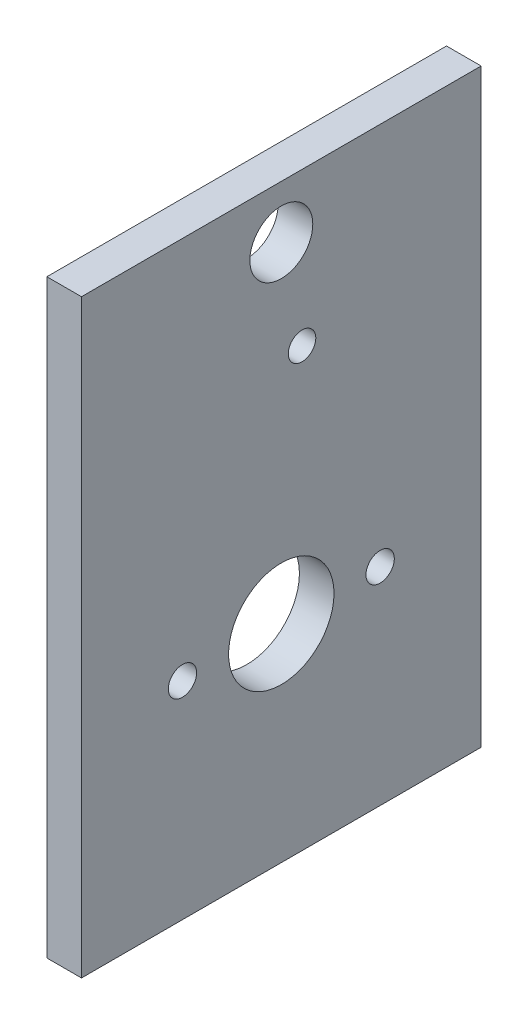
SolidWorks part; units mm, degrees
ref_plane "Front Plane" through (0, 0, 0) normal (0, 0, 1) x (1, 0, 0)
ref_plane "Top Plane" through (0, 0, 0) normal (0, 1, 0) x (1, 0, 0)
ref_plane "Right Plane" through (0, 0, 0) normal (1, 0, 0) x (0, 0, -1)
sketch "Sketch1" plane through (0, 0, 0) normal (1, 0, 0) x (0, 0, -1)
  line L1 (-25.4, -37.5) -> (25.4, -37.5)
  line L2 (-25.4, -37.5) -> (-25.4, 37.5)
  line L3 (-25.4, 37.5) -> (25.4, 37.5)
  line L4 (25.4, -37.5) -> (25.4, 37.5)
  line L5 (-25.4, -37.5) -> (25.4, 37.5) construction
  line L6 (-25.4, 37.5) -> (25.4, -37.5) construction
  point P0 (0, 0)
  dimension "D1" = 75
  dimension "D2" = 50.8
extrude "Boss-Extrude1" add sketch "Sketch1" along normal blind 4.4
sketch "Sketch2" plane through (4.4, 0, 0) normal (1, 0, 0) x (0, 0, -1)
  line L0 (0, 30.7945) -> (0, -11.2055) construction
  line L1 (-12.565, -11.2055) -> (12.565, -11.2055) construction
  circle A0 centre (0, 30.7945) radius 4
  circle A1 centre (0, -11.2055) radius 6.7
  circle A2 centre (-12.565, -11.2055) radius 1.8
  circle A3 centre (12.565, -11.2055) radius 1.8
  point P4 (0, 9.7945)
  point P12 (0, -11.2055)
  dimension "D2" = 8
  dimension "D3" = 13.4
  dimension "D4" = 3.6
  dimension "D1" = 42
  dimension "D5" = 25.13
extrude "Cut-Extrude1" cut sketch "Sketch2" against normal through all
sketch "Sketch3" plane through (4.4, 0, 0) normal (1, 0, 0) x (0, 0, -1)
  line L0 (-2.7972, 25.3736) -> (4.4693, 21.6242)
  line L1 (0, -11.2055) -> (0, 30.7945) construction
  line L2 (3.9905, 14.3062) -> (-7.6753, 10.1044)
  line L3 (0, 18.0695) -> (2.635, 18.0695) construction
  line L4 (0, 24.6945) -> (0, 18.0695) construction
  line L5 (0, 18.0695) -> (0, 11.4445) construction
  line L7 (20.8174, -2.2803) -> (5.6064, 33.1982)
  circle A0 centre (0, 30.7945) radius 6.1 construction
  circle A1 centre (0, -11.2055) radius 22.65 construction
  circle A2 centre (2.635, 18.0695) radius 4 construction
  arc A3 (-2.7972, 25.3736) -> (5.6064, 33.1982) centre (0, 30.7945) cw
  arc A4 (3.9905, 14.3062) -> (4.4693, 21.6242) centre (2.635, 18.0695) ccw
  arc A5 (-7.6753, 10.1044) -> (20.8174, -2.2803) centre (0, -11.2055) ccw
  point P5 (0.9294, 18.275)
  point P13 (2.635, 18.275)
  dimension "D1" = 45.3
  dimension "D2" = 12.2
  dimension "D4" = 42
  dimension "D3" = 8
sketch "Sketch4" plane through (4.4, 0, 0) normal (1, 0, 0) x (0, 0, -1)
  circle A1 centre (2.635, 18.0695) radius 1.75
  dimension "D1" = 3.5
extrude "Cut-Extrude2" cut sketch "Sketch4" against normal through all
equation "\"motor_pulley\"=50"
